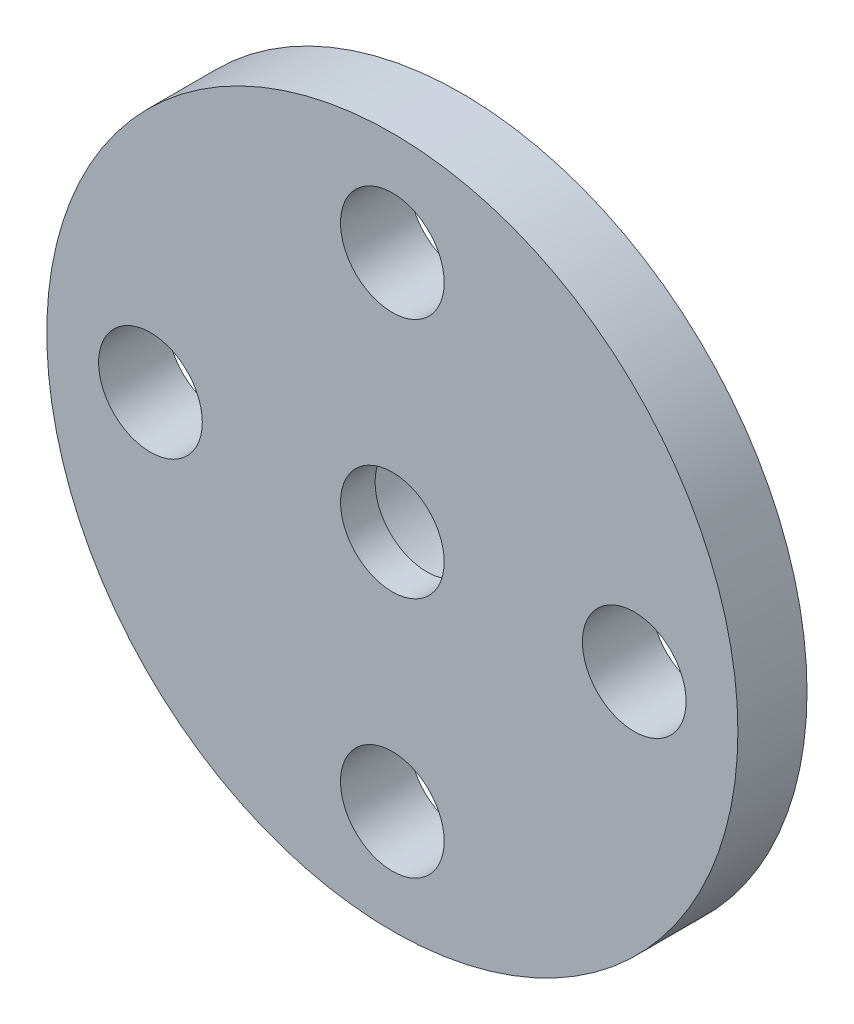
SolidWorks part; units mm, degrees
ref_plane "前视基准面" through (0, 0, 0) normal (0, 0, 1) x (1, 0, 0)
ref_plane "上视基准面" through (0, 0, 0) normal (0, 1, 0) x (1, 0, 0)
ref_plane "右视基准面" through (0, 0, 0) normal (1, 0, 0) x (0, 0, -1)
sketch "草图1" plane through (0, 0, 0) normal (0, 0, 1) x (1, 0, 0)
  line L0 (-7, 0) -> (7, 0) construction
  line L1 (0, 7) -> (0, -7) construction
  circle A0 centre (0, 0) radius 10
  circle A1 centre (0, 0) radius 1.5
  circle A2 centre (-7, 0) radius 1.5
  circle A3 centre (7, 0) radius 1.5
  circle A4 centre (0, 7) radius 1.5
  circle A5 centre (0, -7) radius 1.5
  point P7 (0, 0)
  point P12 (0, 0)
  dimension "D1" = 20
  dimension "D2" = 3
  dimension "D4" = 3
  dimension "D5" = 3
  dimension "D6" = 7
  dimension "D7" = 3
  dimension "D8" = 3
  dimension "D3" = 7
extrude "凸台-拉伸1" add sketch "草图1" along normal blind 2
sketch "草图2" plane through (0, 0, 0) normal (0, 0, 1) x (1, 0, 0)
  circle A0 centre (0, 0) radius 4.5
  circle A1 centre (0, 0) radius 2.75
  dimension "D1" = 9
  dimension "D2" = 5.5
extrude "凸台-拉伸2" add sketch "草图2" against normal blind 2.5
ref_plane "基准面4" through (0, 0, 0) normal (0, 0, -1) x (-1, 0, 0)
sketch "草图3" plane through (0, 0, 0) normal (0, 0, -1) x (-1, 0, 0)
  circle A1 centre (0, 0) radius 2.75
  circle A2 centre (0, 0) radius 2.75
  dimension "D1" = 0
extrude "切除-拉伸1" cut sketch "草图3" against normal blind 1
